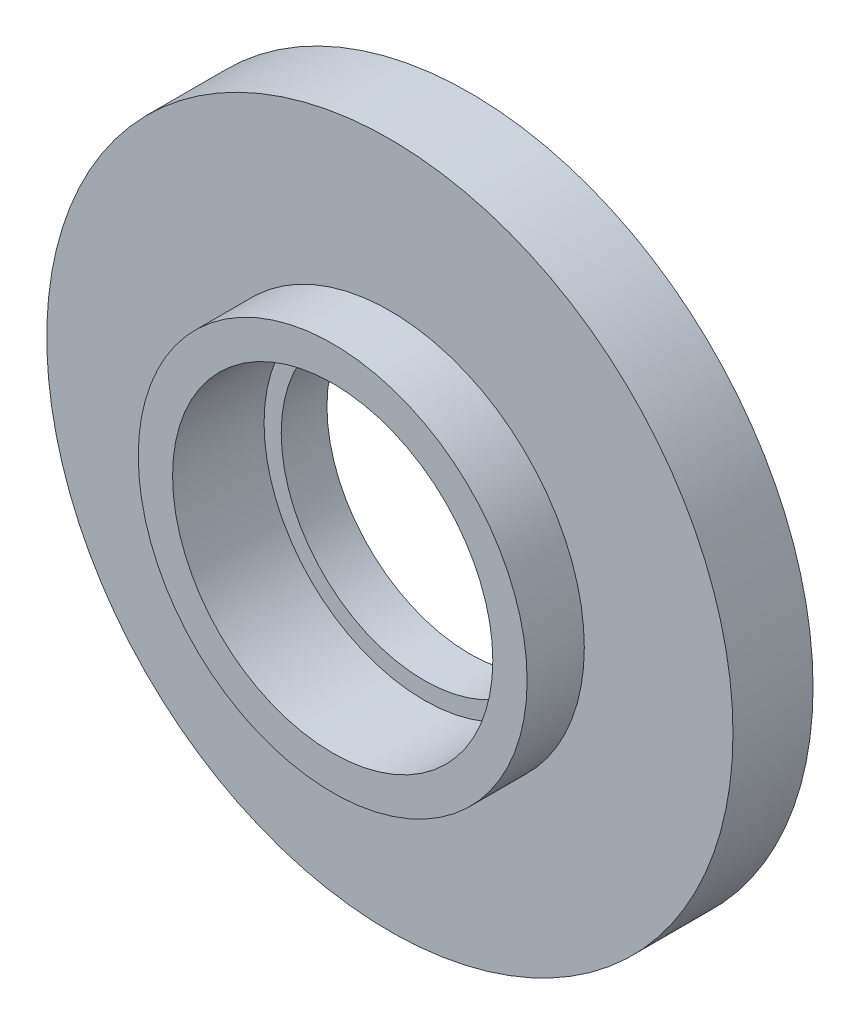
SolidWorks part; units mm, degrees
ref_plane "Front Plane" through (0, 0, 0) normal (0, 0, 1) x (1, 0, 0)
ref_plane "Top Plane" through (0, 0, 0) normal (0, 1, 0) x (1, 0, 0)
ref_plane "Right Plane" through (0, 0, 0) normal (1, 0, 0) x (0, 0, -1)
sketch "Sketch2" plane through (0, 0, 0) normal (0, 1, 0) x (1, 0, 0)
  line L0 (0, 0) -> (-30, 0)
  line L1 (-30, 0) -> (-30, -7)
  line L2 (-30, -7) -> (-17, -7)
  line L3 (-17, -7) -> (-17, -12)
  line L4 (-17, -12) -> (0, -12)
  line L5 (0, -12) -> (0, 0)
  dimension "D1" = 7
  dimension "D2" = 5
  dimension "D3" = 30
  dimension "D4" = 17
revolve "Revolve4" add sketch "Sketch2" angle 360 about L5
sketch "Sketch4" plane through (0, 0, 12) normal (0, 0, 1) x (1, 0, 0)
  circle A0 centre (0, 0) radius 14
  dimension "D1" = 28
extrude "Cut-Extrude1" cut sketch "Sketch4" against normal blind 8
sketch "Sketch5" plane through (0, 0, 0) normal (0, 0, -1) x (-1, 0, 0)
  circle A0 centre (0, 0) radius 12.5
  dimension "D1" = 25
extrude "Cut-Extrude4" cut sketch "Sketch5" against normal blind 8.1
sketch "Sketch7" plane through (0, 0, 0) normal (0, 0, -1) x (-1, 0, 0)
  circle A1 centre (0, 18) radius 2.5
  circle A7 centre (15.5885, 9) radius 2.5
  circle A8 centre (15.5885, -9) radius 2.5
  circle A9 centre (0, -18) radius 2.5
  circle A10 centre (-15.5885, -9) radius 2.5
  circle A11 centre (-15.5885, 9) radius 2.5
  point P14 (0, 0)
  point P15 (0, 0)
  dimension "D1" = 5
  dimension "D2" = 18
  dimension "D3" = 6
extrude "Cut-Extrude5" cut sketch "Sketch7" against normal blind 3
